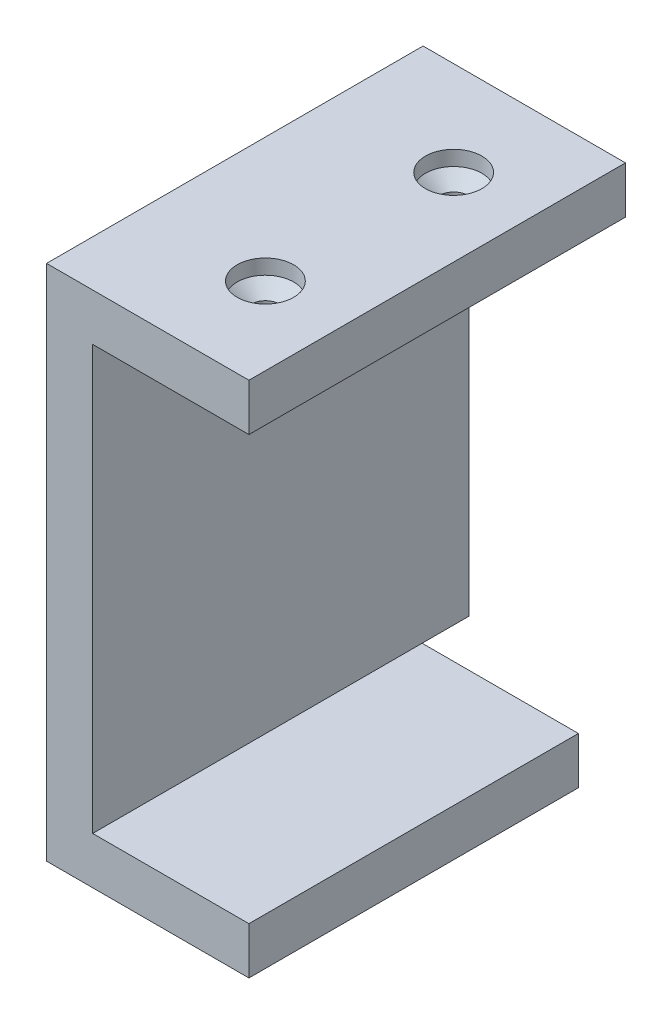
SolidWorks part; units mm, degrees
ref_plane "Front Plane" through (0, 0, 0) normal (0, 0, 1) x (1, 0, 0)
ref_plane "Top Plane" through (0, 0, 0) normal (0, 1, 0) x (1, 0, 0)
ref_plane "Right Plane" through (0, 0, 0) normal (1, 0, 0) x (0, 0, -1)
sketch "Sketch1" plane through (0, 0, 0) normal (0, 1, 0) x (1, 0, 0)
  line L0 (-7.5, -20) -> (9, -20)
  line L2 (9, -20) -> (9, 20)
  line L3 (-7.5, 20) -> (9, 20)
  line L4 (-7.5, -20) -> (9, 20) construction
  line L5 (9, -20) -> (-7.5, 20) construction
  line L6 (-12.5, 20) -> (-7.5, 20)
  line L10 (-12.5, 20) -> (-12.5, -20)
  line L11 (-7.5, -20) -> (-12.5, -20)
  point P1 (0, 0)
  point P3 (0, 0)
  point P9 (0, 0)
  point P10 (0, 0)
  point P11 (0, 0)
  point P12 (0, 0)
extrude "Boss-Extrude1" add sketch "Sketch1" along normal blind 5
sketch "Sketch2" plane through (0, 0, 0) normal (0, 1, 0) x (1, 0, 0)
  line L1 (-7.6, 20) -> (-12.5, 20)
  line L2 (-7.6, 20) -> (-7.6, -20)
  line L3 (-7.6, -20) -> (-12.5, -20)
  line L4 (-12.5, 20) -> (-12.5, -20)
extrude "Boss-Extrude2" add sketch "Sketch2" against normal blind 45
sketch "Sketch3" plane through (0, -45, 0) normal (0, -1, 0) x (1, 0, 0)
  line L1 (-12.5, -15) -> (9, -15)
  line L2 (-12.5, -15) -> (-12.5, 20)
  line L3 (-12.5, 20) -> (9, 20)
  line L4 (9, -15) -> (9, 20)
  point P6 (0, 0)
  point P7 (0, 0)
extrude "Boss-Extrude3" add sketch "Sketch3" along normal blind 5
sketch "Sketch4" plane through (0, 0, 0) normal (0, -1, 0) x (1, 0, 0)
  line L0 (9, -20) -> (-7.5, -20) construction
  line L1 (11.825, 0) -> (-11.825, 0) construction
  line L2 (9, -20) -> (-12.5, -20) construction
  line L3 (0.75, -20) -> (0.75, 20) construction
  line L4 (-12.5, 20) -> (9, 20) construction
  line L5 (13.71, -10) -> (-15.9224, -10) construction
  circle A2 centre (0.75, -10) radius 3
  circle A3 centre (0.75, 10) radius 3
  point P15 (0, 0)
  point P16 (0.75, -10)
extrude "Cut-Extrude1" cut sketch "Sketch4" against normal blind 5
ref_axis "Axis2" through (0.75, 5, 10) along (0, -1, 0)
ref_plane "Plane1" through (0.75, 0, 0) normal (-1, 0, 0) x (0, -1, 0)
sketch "Sketch5" plane through (0.75, 0, 0) normal (-1, 0, 0) x (0, -1, 0)
  line L0 (-3.415, 13) -> (-2.115, 11.5256)
  line L2 (0, 11.5256) -> (0, 13)
  line L4 (-2.115, 11.5256) -> (1, 11.5256)
  line L5 (1, 8.3) -> (-2.115, 8.3)
  line L7 (-2.115, 11.5256) -> (0, 11.5256)
  line L8 (-3.415, 13) -> (0, 13)
revolve "Revolve1" add sketch "Sketch5" angle 360 about axis through (0.75, 5, 10) along (0, -1, 0)
mirror "Mirror1" about plane through (0, 0, 0) normal (0, 0, 1) of "Revolve1"
